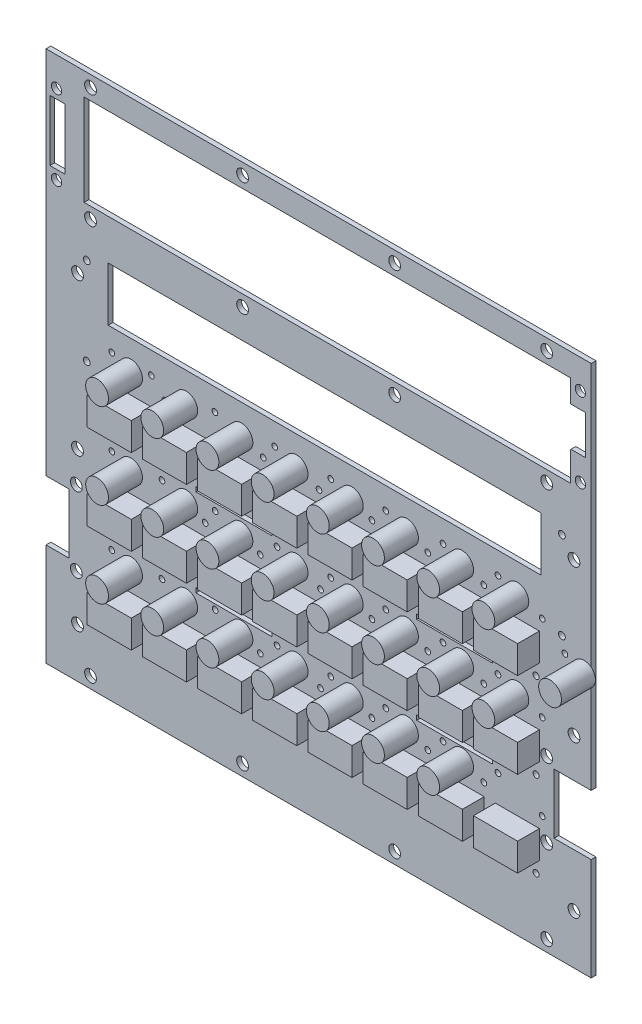
SolidWorks part; units mm, degrees
ref_plane "Front Plane" through (0, 0, 0) normal (0, 0, 1) x (1, 0, 0)
ref_plane "Top Plane" through (0, 0, 0) normal (0, 1, 0) x (1, 0, 0)
ref_plane "Right Plane" through (0, 0, 0) normal (1, 0, 0) x (0, 0, -1)
sketch "Sketch1" plane through (0, 0, 0) normal (0, 0, 1) x (1, 0, 0)
  line L0 (0, 0) -> (182.118, 0)
  line L1 (182.118, 0) -> (182.118, 34.2468)
  line L2 (182.118, 34.2468) -> (169.7355, 34.2468)
  line L3 (169.7355, 34.2468) -> (169.7355, 54.2468)
  line L4 (169.7355, 54.2468) -> (182.118, 54.2468)
  line L5 (182.118, 54.2468) -> (182.118, 177.8)
  line L6 (182.118, 177.8) -> (0, 177.8)
  line L7 (0, 177.8) -> (0, 54.2468)
  line L8 (0, 54.2468) -> (7.62, 54.2468)
  line L9 (7.62, 54.2468) -> (7.62, 34.2468)
  line L10 (7.62, 34.2468) -> (0, 34.2468)
  line L11 (0, 34.2468) -> (0, 0)
  line L12 (20.7391, 108.1786) -> (20.7391, 126.1796)
  line L13 (20.7391, 126.1796) -> (165.3007, 126.1796)
  line L14 (165.3007, 126.1796) -> (165.3007, 108.1786)
  line L15 (165.3007, 108.1786) -> (20.7391, 108.1786)
  line L16 (1.27, 144.653) -> (1.27, 164.973)
  line L17 (1.27, 164.973) -> (6.35, 164.973)
  line L18 (6.35, 164.973) -> (6.35, 144.653)
  line L19 (6.35, 144.653) -> (1.27, 144.653)
  line L20 (12.7, 139.7) -> (12.7, 170.18)
  line L21 (12.7, 170.18) -> (175.26, 170.18)
  line L22 (175.26, 170.18) -> (175.26, 162.6616)
  line L23 (175.26, 162.6616) -> (180.086, 162.6616)
  line L24 (180.086, 162.6616) -> (180.2892, 162.4584)
  line L25 (180.2892, 162.4584) -> (180.2892, 149.606)
  line L26 (180.2892, 149.606) -> (175.3616, 149.606)
  line L27 (175.3616, 149.606) -> (175.26, 149.5044)
  line L28 (175.26, 149.5044) -> (175.26, 139.7)
  line L29 (175.26, 139.7) -> (12.7, 139.7)
  line L30 (50.0634, 45.4152) -> (50.0634, 47.0027)
  line L31 (50.0634, 47.0027) -> (75.4634, 47.0027)
  line L32 (75.4634, 47.0027) -> (75.4634, 45.4152)
  line L33 (75.4634, 45.4152) -> (50.0634, 45.4152)
  line L34 (123.8134, 45.4152) -> (123.8134, 47.0027)
  line L35 (123.8134, 47.0027) -> (149.2134, 47.0027)
  line L36 (149.2134, 47.0027) -> (149.2134, 45.4152)
  line L37 (149.2134, 45.4152) -> (123.8134, 45.4152)
  line L38 (123.8134, 74.6252) -> (123.8134, 76.2127)
  line L39 (123.8134, 76.2127) -> (149.2134, 76.2127)
  line L40 (149.2134, 76.2127) -> (149.2134, 74.6252)
  line L41 (149.2134, 74.6252) -> (123.8134, 74.6252)
  line L42 (50.0634, 74.6252) -> (50.0634, 76.2127)
  line L43 (50.0634, 76.2127) -> (75.4634, 76.2127)
  line L44 (75.4634, 76.2127) -> (75.4634, 74.6252)
  line L45 (75.4634, 74.6252) -> (50.0634, 74.6252)
extrude "BOARD" add sketch "Sketch1" along normal blind 1.5921 separate body
ref_plane "Plane1" through (0, 0, 1.5921) normal (0, 0, 1) x (1, 0, 0)
sketch "Sketch2" plane through (0, 0, 1.5921) normal (0, 0, 1) x (1, 0, 0)
  circle A0 centre (179.7355, 86.9188) radius 3.81
extrude "LED-KINGBRIGHT_3P_2P54-1" add sketch "Sketch2" along normal blind 11.3538 separate body
sketch "Sketch4" plane through (0, 0, 1.5921) normal (0, 0, 1) x (1, 0, 0)
  circle A0 centre (139.0222, 41.1988) radius 3.81
extrude "LED-KINGBRIGHT_3P_2P54-3" add sketch "Sketch4" along normal blind 11.3538 separate body
sketch "Sketch5" plane through (0, 0, 1.5921) normal (0, 0, 1) x (1, 0, 0)
  circle A0 centre (120.5847, 41.1988) radius 3.81
extrude "LED-KINGBRIGHT_3P_2P54-4" add sketch "Sketch5" along normal blind 11.3538 separate body
sketch "Sketch6" plane through (0, 0, 1.5921) normal (0, 0, 1) x (1, 0, 0)
  circle A0 centre (102.1472, 41.1988) radius 3.81
extrude "LED-KINGBRIGHT_3P_2P54-5" add sketch "Sketch6" along normal blind 11.3538 separate body
sketch "Sketch7" plane through (0, 0, 1.5921) normal (0, 0, 1) x (1, 0, 0)
  circle A0 centre (157.4597, 69.7738) radius 3.81
extrude "LED-KINGBRIGHT_3P_2P54-6" add sketch "Sketch7" along normal blind 11.3538 separate body
sketch "Sketch8" plane through (0, 0, 1.5921) normal (0, 0, 1) x (1, 0, 0)
  circle A0 centre (139.0222, 69.7738) radius 3.81
extrude "LED-KINGBRIGHT_3P_2P54-7" add sketch "Sketch8" along normal blind 11.3538 separate body
sketch "Sketch9" plane through (0, 0, 1.5921) normal (0, 0, 1) x (1, 0, 0)
  circle A0 centre (120.5847, 69.7738) radius 3.81
extrude "LED-KINGBRIGHT_3P_2P54-8" add sketch "Sketch9" along normal blind 11.3538 separate body
sketch "Sketch10" plane through (0, 0, 1.5921) normal (0, 0, 1) x (1, 0, 0)
  circle A0 centre (102.1472, 69.7738) radius 3.81
extrude "LED-KINGBRIGHT_3P_2P54-9" add sketch "Sketch10" along normal blind 11.3538 separate body
sketch "Sketch11" plane through (0, 0, 1.5921) normal (0, 0, 1) x (1, 0, 0)
  circle A0 centre (83.7097, 41.1988) radius 3.81
extrude "LED-KINGBRIGHT_3P_2P54-10" add sketch "Sketch11" along normal blind 11.3538 separate body
sketch "Sketch12" plane through (0, 0, 1.5921) normal (0, 0, 1) x (1, 0, 0)
  circle A0 centre (65.2722, 41.1988) radius 3.81
extrude "LED-KINGBRIGHT_3P_2P54-11" add sketch "Sketch12" along normal blind 11.3538 separate body
sketch "Sketch13" plane through (0, 0, 1.5921) normal (0, 0, 1) x (1, 0, 0)
  circle A0 centre (46.8347, 41.1988) radius 3.81
extrude "LED-KINGBRIGHT_3P_2P54-12" add sketch "Sketch13" along normal blind 11.3538 separate body
sketch "Sketch14" plane through (0, 0, 1.5921) normal (0, 0, 1) x (1, 0, 0)
  circle A0 centre (28.3972, 41.1988) radius 3.81
extrude "LED-KINGBRIGHT_3P_2P54-13" add sketch "Sketch14" along normal blind 11.3538 separate body
sketch "Sketch15" plane through (0, 0, 1.5921) normal (0, 0, 1) x (1, 0, 0)
  circle A0 centre (83.7097, 69.7738) radius 3.81
extrude "LED-KINGBRIGHT_3P_2P54-14" add sketch "Sketch15" along normal blind 11.3538 separate body
sketch "Sketch16" plane through (0, 0, 1.5921) normal (0, 0, 1) x (1, 0, 0)
  circle A0 centre (65.2722, 69.7738) radius 3.81
extrude "LED-KINGBRIGHT_3P_2P54-15" add sketch "Sketch16" along normal blind 11.3538 separate body
sketch "Sketch17" plane through (0, 0, 1.5921) normal (0, 0, 1) x (1, 0, 0)
  circle A0 centre (46.8347, 69.7738) radius 3.81
extrude "LED-KINGBRIGHT_3P_2P54-16" add sketch "Sketch17" along normal blind 11.3538 separate body
sketch "Sketch18" plane through (0, 0, 1.5921) normal (0, 0, 1) x (1, 0, 0)
  circle A0 centre (28.3972, 69.7738) radius 3.81
extrude "LED-KINGBRIGHT_3P_2P54-17" add sketch "Sketch18" along normal blind 11.3538 separate body
sketch "Sketch19" plane through (0, 0, 1.5921) normal (0, 0, 1) x (1, 0, 0)
  circle A0 centre (157.4597, 98.3488) radius 3.81
extrude "LED-KINGBRIGHT_3P_2P54-18" add sketch "Sketch19" along normal blind 11.3538 separate body
sketch "Sketch20" plane through (0, 0, 1.5921) normal (0, 0, 1) x (1, 0, 0)
  circle A0 centre (139.0222, 98.3488) radius 3.81
extrude "LED-KINGBRIGHT_3P_2P54-19" add sketch "Sketch20" along normal blind 11.3538 separate body
sketch "Sketch21" plane through (0, 0, 1.5921) normal (0, 0, 1) x (1, 0, 0)
  circle A0 centre (120.5847, 98.3488) radius 3.81
extrude "LED-KINGBRIGHT_3P_2P54-20" add sketch "Sketch21" along normal blind 11.3538 separate body
sketch "Sketch22" plane through (0, 0, 1.5921) normal (0, 0, 1) x (1, 0, 0)
  circle A0 centre (102.1472, 98.3488) radius 3.81
extrude "LED-KINGBRIGHT_3P_2P54-21" add sketch "Sketch22" along normal blind 11.3538 separate body
sketch "Sketch23" plane through (0, 0, 1.5921) normal (0, 0, 1) x (1, 0, 0)
  circle A0 centre (83.7097, 98.3488) radius 3.81
extrude "LED-KINGBRIGHT_3P_2P54-22" add sketch "Sketch23" along normal blind 11.3538 separate body
sketch "Sketch24" plane through (0, 0, 1.5921) normal (0, 0, 1) x (1, 0, 0)
  circle A0 centre (65.2722, 98.3488) radius 3.81
extrude "LED-KINGBRIGHT_3P_2P54-23" add sketch "Sketch24" along normal blind 11.3538 separate body
sketch "Sketch25" plane through (0, 0, 1.5921) normal (0, 0, 1) x (1, 0, 0)
  circle A0 centre (46.8347, 98.3488) radius 3.81
extrude "LED-KINGBRIGHT_3P_2P54-24" add sketch "Sketch25" along normal blind 11.3538 separate body
sketch "Sketch26" plane through (0, 0, 1.5921) normal (0, 0, 1) x (1, 0, 0)
  circle A0 centre (28.3972, 98.3488) radius 3.81
extrude "LED-KINGBRIGHT_3P_2P54-25" add sketch "Sketch26" along normal blind 11.3538 separate body
sketch "Sketch27" plane through (0, 0, 1.5921) normal (0, 0, 1) x (1, 0, 0)
  line L0 (150.0937, 25.3238) -> (150.0937, 34.5948)
  line L1 (150.0937, 34.5948) -> (164.8257, 34.5948)
  line L2 (164.8257, 34.5948) -> (164.8257, 25.3238)
  line L3 (164.8257, 25.3238) -> (150.0937, 25.3238)
extrude "SWITCH-MCDTS2-1" add sketch "Sketch27" along normal blind 7.3 separate body
sketch "Sketch28" plane through (0, 0, 1.5921) normal (0, 0, 1) x (1, 0, 0)
  line L0 (150.0937, 53.8988) -> (150.0937, 63.1698)
  line L1 (150.0937, 63.1698) -> (164.8257, 63.1698)
  line L2 (164.8257, 63.1698) -> (164.8257, 53.8988)
  line L3 (164.8257, 53.8988) -> (150.0937, 53.8988)
extrude "SWITCH-MCDTS2-2" add sketch "Sketch28" along normal blind 7.3 separate body
sketch "Sketch29" plane through (0, 0, 1.5921) normal (0, 0, 1) x (1, 0, 0)
  line L0 (131.6562, 25.3238) -> (131.6562, 34.5948)
  line L1 (131.6562, 34.5948) -> (146.3882, 34.5948)
  line L2 (146.3882, 34.5948) -> (146.3882, 25.3238)
  line L3 (146.3882, 25.3238) -> (131.6562, 25.3238)
extrude "SWITCH-MCDTS2-3" add sketch "Sketch29" along normal blind 7.3 separate body
sketch "Sketch30" plane through (0, 0, 1.5921) normal (0, 0, 1) x (1, 0, 0)
  line L0 (113.2187, 25.3238) -> (113.2187, 34.5948)
  line L1 (113.2187, 34.5948) -> (127.9507, 34.5948)
  line L2 (127.9507, 34.5948) -> (127.9507, 25.3238)
  line L3 (127.9507, 25.3238) -> (113.2187, 25.3238)
extrude "SWITCH-MCDTS2-4" add sketch "Sketch30" along normal blind 7.3 separate body
sketch "Sketch31" plane through (0, 0, 1.5921) normal (0, 0, 1) x (1, 0, 0)
  line L0 (94.7812, 25.3238) -> (94.7812, 34.5948)
  line L1 (94.7812, 34.5948) -> (109.5132, 34.5948)
  line L2 (109.5132, 34.5948) -> (109.5132, 25.3238)
  line L3 (109.5132, 25.3238) -> (94.7812, 25.3238)
extrude "SWITCH-MCDTS2-5" add sketch "Sketch31" along normal blind 7.3 separate body
sketch "Sketch32" plane through (0, 0, 1.5921) normal (0, 0, 1) x (1, 0, 0)
  line L0 (76.3437, 25.3238) -> (76.3437, 34.5948)
  line L1 (76.3437, 34.5948) -> (91.0757, 34.5948)
  line L2 (91.0757, 34.5948) -> (91.0757, 25.3238)
  line L3 (91.0757, 25.3238) -> (76.3437, 25.3238)
extrude "SWITCH-MCDTS2-6" add sketch "Sketch32" along normal blind 7.3 separate body
sketch "Sketch33" plane through (0, 0, 1.5921) normal (0, 0, 1) x (1, 0, 0)
  line L0 (57.9062, 25.3238) -> (57.9062, 34.5948)
  line L1 (57.9062, 34.5948) -> (72.6382, 34.5948)
  line L2 (72.6382, 34.5948) -> (72.6382, 25.3238)
  line L3 (72.6382, 25.3238) -> (57.9062, 25.3238)
extrude "SWITCH-MCDTS2-7" add sketch "Sketch33" along normal blind 7.3 separate body
sketch "Sketch34" plane through (0, 0, 1.5921) normal (0, 0, 1) x (1, 0, 0)
  line L0 (39.4687, 25.3238) -> (39.4687, 34.5948)
  line L1 (39.4687, 34.5948) -> (54.2007, 34.5948)
  line L2 (54.2007, 34.5948) -> (54.2007, 25.3238)
  line L3 (54.2007, 25.3238) -> (39.4687, 25.3238)
extrude "SWITCH-MCDTS2-8" add sketch "Sketch34" along normal blind 7.3 separate body
sketch "Sketch35" plane through (0, 0, 1.5921) normal (0, 0, 1) x (1, 0, 0)
  line L0 (21.0312, 25.3238) -> (21.0312, 34.5948)
  line L1 (21.0312, 34.5948) -> (35.7632, 34.5948)
  line L2 (35.7632, 34.5948) -> (35.7632, 25.3238)
  line L3 (35.7632, 25.3238) -> (21.0312, 25.3238)
extrude "SWITCH-MCDTS2-9" add sketch "Sketch35" along normal blind 7.3 separate body
sketch "Sketch36" plane through (0, 0, 1.5921) normal (0, 0, 1) x (1, 0, 0)
  line L0 (131.6562, 53.8988) -> (131.6562, 63.1698)
  line L1 (131.6562, 63.1698) -> (146.3882, 63.1698)
  line L2 (146.3882, 63.1698) -> (146.3882, 53.8988)
  line L3 (146.3882, 53.8988) -> (131.6562, 53.8988)
extrude "SWITCH-MCDTS2-10" add sketch "Sketch36" along normal blind 7.3 separate body
sketch "Sketch37" plane through (0, 0, 1.5921) normal (0, 0, 1) x (1, 0, 0)
  line L0 (113.2187, 53.8988) -> (113.2187, 63.1698)
  line L1 (113.2187, 63.1698) -> (127.9507, 63.1698)
  line L2 (127.9507, 63.1698) -> (127.9507, 53.8988)
  line L3 (127.9507, 53.8988) -> (113.2187, 53.8988)
extrude "SWITCH-MCDTS2-11" add sketch "Sketch37" along normal blind 7.3 separate body
sketch "Sketch38" plane through (0, 0, 1.5921) normal (0, 0, 1) x (1, 0, 0)
  line L0 (94.7812, 53.8988) -> (94.7812, 63.1698)
  line L1 (94.7812, 63.1698) -> (109.5132, 63.1698)
  line L2 (109.5132, 63.1698) -> (109.5132, 53.8988)
  line L3 (109.5132, 53.8988) -> (94.7812, 53.8988)
extrude "SWITCH-MCDTS2-12" add sketch "Sketch38" along normal blind 7.3 separate body
sketch "Sketch39" plane through (0, 0, 1.5921) normal (0, 0, 1) x (1, 0, 0)
  line L0 (76.3437, 53.8988) -> (76.3437, 63.1698)
  line L1 (76.3437, 63.1698) -> (91.0757, 63.1698)
  line L2 (91.0757, 63.1698) -> (91.0757, 53.8988)
  line L3 (91.0757, 53.8988) -> (76.3437, 53.8988)
extrude "SWITCH-MCDTS2-13" add sketch "Sketch39" along normal blind 7.3 separate body
sketch "Sketch40" plane through (0, 0, 1.5921) normal (0, 0, 1) x (1, 0, 0)
  line L0 (57.9062, 53.8988) -> (57.9062, 63.1698)
  line L1 (57.9062, 63.1698) -> (72.6382, 63.1698)
  line L2 (72.6382, 63.1698) -> (72.6382, 53.8988)
  line L3 (72.6382, 53.8988) -> (57.9062, 53.8988)
extrude "SWITCH-MCDTS2-14" add sketch "Sketch40" along normal blind 7.3 separate body
sketch "Sketch41" plane through (0, 0, 1.5921) normal (0, 0, 1) x (1, 0, 0)
  line L0 (39.4687, 53.8988) -> (39.4687, 63.1698)
  line L1 (39.4687, 63.1698) -> (54.2007, 63.1698)
  line L2 (54.2007, 63.1698) -> (54.2007, 53.8988)
  line L3 (54.2007, 53.8988) -> (39.4687, 53.8988)
extrude "SWITCH-MCDTS2-15" add sketch "Sketch41" along normal blind 7.3 separate body
sketch "Sketch42" plane through (0, 0, 1.5921) normal (0, 0, 1) x (1, 0, 0)
  line L0 (21.0312, 53.8988) -> (21.0312, 63.1698)
  line L1 (21.0312, 63.1698) -> (35.7632, 63.1698)
  line L2 (35.7632, 63.1698) -> (35.7632, 53.8988)
  line L3 (35.7632, 53.8988) -> (21.0312, 53.8988)
extrude "SWITCH-MCDTS2-16" add sketch "Sketch42" along normal blind 7.3 separate body
sketch "Sketch43" plane through (0, 0, 1.5921) normal (0, 0, 1) x (1, 0, 0)
  line L0 (150.0937, 82.4738) -> (150.0937, 91.7448)
  line L1 (150.0937, 91.7448) -> (164.8257, 91.7448)
  line L2 (164.8257, 91.7448) -> (164.8257, 82.4738)
  line L3 (164.8257, 82.4738) -> (150.0937, 82.4738)
extrude "SWITCH-MCDTS2-17" add sketch "Sketch43" along normal blind 7.3 separate body
sketch "Sketch44" plane through (0, 0, 1.5921) normal (0, 0, 1) x (1, 0, 0)
  line L0 (131.6562, 82.4738) -> (131.6562, 91.7448)
  line L1 (131.6562, 91.7448) -> (146.3882, 91.7448)
  line L2 (146.3882, 91.7448) -> (146.3882, 82.4738)
  line L3 (146.3882, 82.4738) -> (131.6562, 82.4738)
extrude "SWITCH-MCDTS2-18" add sketch "Sketch44" along normal blind 7.3 separate body
sketch "Sketch45" plane through (0, 0, 1.5921) normal (0, 0, 1) x (1, 0, 0)
  line L0 (113.2187, 82.4738) -> (113.2187, 91.7448)
  line L1 (113.2187, 91.7448) -> (127.9507, 91.7448)
  line L2 (127.9507, 91.7448) -> (127.9507, 82.4738)
  line L3 (127.9507, 82.4738) -> (113.2187, 82.4738)
extrude "SWITCH-MCDTS2-19" add sketch "Sketch45" along normal blind 7.3 separate body
sketch "Sketch46" plane through (0, 0, 1.5921) normal (0, 0, 1) x (1, 0, 0)
  line L0 (94.7812, 82.4738) -> (94.7812, 91.7448)
  line L1 (94.7812, 91.7448) -> (109.5132, 91.7448)
  line L2 (109.5132, 91.7448) -> (109.5132, 82.4738)
  line L3 (109.5132, 82.4738) -> (94.7812, 82.4738)
extrude "SWITCH-MCDTS2-20" add sketch "Sketch46" along normal blind 7.3 separate body
sketch "Sketch47" plane through (0, 0, 1.5921) normal (0, 0, 1) x (1, 0, 0)
  line L0 (76.3437, 82.4738) -> (76.3437, 91.7448)
  line L1 (76.3437, 91.7448) -> (91.0757, 91.7448)
  line L2 (91.0757, 91.7448) -> (91.0757, 82.4738)
  line L3 (91.0757, 82.4738) -> (76.3437, 82.4738)
extrude "SWITCH-MCDTS2-21" add sketch "Sketch47" along normal blind 7.3 separate body
sketch "Sketch48" plane through (0, 0, 1.5921) normal (0, 0, 1) x (1, 0, 0)
  line L0 (57.9062, 82.4738) -> (57.9062, 91.7448)
  line L1 (57.9062, 91.7448) -> (72.6382, 91.7448)
  line L2 (72.6382, 91.7448) -> (72.6382, 82.4738)
  line L3 (72.6382, 82.4738) -> (57.9062, 82.4738)
extrude "SWITCH-MCDTS2-22" add sketch "Sketch48" along normal blind 7.3 separate body
sketch "Sketch49" plane through (0, 0, 1.5921) normal (0, 0, 1) x (1, 0, 0)
  line L0 (39.4687, 82.4738) -> (39.4687, 91.7448)
  line L1 (39.4687, 91.7448) -> (54.2007, 91.7448)
  line L2 (54.2007, 91.7448) -> (54.2007, 82.4738)
  line L3 (54.2007, 82.4738) -> (39.4687, 82.4738)
extrude "SWITCH-MCDTS2-23" add sketch "Sketch49" along normal blind 7.3 separate body
sketch "Sketch50" plane through (0, 0, 1.5921) normal (0, 0, 1) x (1, 0, 0)
  line L0 (21.0312, 82.4738) -> (21.0312, 91.7448)
  line L1 (21.0312, 91.7448) -> (35.7632, 91.7448)
  line L2 (35.7632, 91.7448) -> (35.7632, 82.4738)
  line L3 (35.7632, 82.4738) -> (21.0312, 82.4738)
extrude "SWITCH-MCDTS2-24" add sketch "Sketch50" along normal blind 7.3 separate body
sketch "Sketch59" plane through (0, 0, 1.5921) normal (0, 0, 1) x (1, 0, 0)
  circle B0 centre (163.703, 21.1074) radius 1.016
  circle B1 centre (163.703, 49.6824) radius 1.016
  circle B2 centre (145.2626, 21.8186) radius 0.9652
  circle B3 centre (126.8476, 21.6154) radius 0.9652
  circle B4 centre (108.4072, 21.7424) radius 0.9652
  circle B5 centre (89.9668, 21.844) radius 0.9652
  circle B6 centre (71.5264, 20.7772) radius 0.9652
  circle B7 centre (53.086, 21.1582) radius 0.9652
  circle B8 centre (34.6472, 21.1328) radius 1.016
  circle B9 centre (145.2626, 49.5554) radius 1.016
  circle B10 centre (126.8222, 49.3522) radius 1.016
  circle B11 centre (108.3818, 49.1236) radius 1.016
  circle B12 centre (89.9414, 49.6824) radius 1.016
  circle B13 centre (71.501, 49.1998) radius 1.016
  circle B14 centre (53.0606, 49.1998) radius 1.016
  circle B15 centre (34.6202, 49.276) radius 1.016
  circle B16 centre (163.703, 78.2574) radius 1.016
  circle B17 centre (145.2626, 77.7748) radius 1.016
  circle B18 centre (126.746, 78.3336) radius 1.016
  circle B19 centre (108.3818, 78.74) radius 1.016
  circle B20 centre (89.9414, 78.3336) radius 1.016
  circle B21 centre (71.501, 78.2574) radius 1.016
  circle B22 centre (53.0606, 78.4098) radius 1.016
  circle B23 centre (34.6202, 78.0542) radius 1.016
  circle B24 centre (91.694, 38.6588) radius 0.9525
  circle B25 centre (77.1652, 43.7388) radius 0.9525
  circle B26 centre (71.5772, 38.6588) radius 0.9525
  circle B27 centre (56.4896, 43.7388) radius 0.9525
  circle B28 centre (38.735, 43.7388) radius 0.9525
  circle B29 centre (21.8948, 38.6588) radius 0.9525
  circle B30 centre (21.971, 43.7388) radius 0.9525
  circle B31 centre (77.1652, 72.3138) radius 0.9525
  circle B32 centre (91.694, 67.2338) radius 0.9525
  circle B33 centre (71.5772, 67.2338) radius 0.9525
  circle B34 centre (56.4896, 72.3138) radius 0.9525
  circle B35 centre (53.1368, 67.2338) radius 0.9525
  circle B36 centre (38.735, 72.3138) radius 0.9525
  circle B37 centre (21.8948, 67.2338) radius 0.9525
  circle B38 centre (21.971, 72.3138) radius 0.9525
  circle B39 centre (165.735, 95.8088) radius 0.9525
  circle B40 centre (150.9776, 100.8888) radius 0.9525
  circle B41 centre (146.2278, 95.8088) radius 0.9525
  circle B42 centre (132.6134, 100.8888) radius 0.9525
  circle B43 centre (113.4872, 100.8888) radius 0.9525
  circle B44 centre (127.508, 95.8088) radius 0.9525
  circle B45 centre (108.8644, 95.8088) radius 0.9525
  circle B46 centre (95.0976, 100.8888) radius 0.9525
  circle B47 centre (91.186, 95.8088) radius 0.9525
  circle B48 centre (76.3778, 100.8888) radius 0.9525
  circle B49 centre (72.5424, 95.8088) radius 0.9525
  circle B50 centre (56.4134, 100.8888) radius 0.9525
  circle B51 centre (39.7256, 95.8088) radius 0.9525
  circle B52 centre (35.179, 100.8888) radius 0.9525
  circle B53 centre (24.2062, 95.8088) radius 0.9525
  circle B54 centre (21.971, 100.8888) radius 0.9525
  circle B55 centre (132.6134, 72.3138) radius 0.9525
  circle B56 centre (146.2278, 67.2338) radius 0.9525
  circle B57 centre (113.4872, 72.3138) radius 0.9525
  circle B58 centre (127.508, 67.2338) radius 0.9525
  circle B59 centre (95.0976, 72.3138) radius 0.9525
  circle B60 centre (108.8644, 67.2338) radius 0.9525
  circle B61 centre (173.3296, 89.4588) radius 0.9525
  circle B62 centre (150.9776, 43.7388) radius 0.9525
  circle B63 centre (132.6134, 43.7388) radius 0.9525
  circle B64 centre (113.4872, 43.7388) radius 0.9525
  circle B65 centre (95.0976, 43.7388) radius 0.9525
  circle B66 centre (108.8644, 38.6588) radius 0.9525
  circle B67 centre (150.9776, 72.3138) radius 0.9525
  circle B68 centre (165.735, 67.2338) radius 0.9525
  circle B69 centre (173.355, 84.3534) radius 0.9525
  circle B70 centre (176.3725, 118.11) radius 1.9685
  circle B71 centre (176.3725, 67.31) radius 1.9685
  circle B72 centre (176.3725, 16.51) radius 1.9685
  circle B73 centre (167.259, 135.89) radius 1.9685
  circle B74 centre (116.459, 135.89) radius 1.9685
  circle B75 centre (65.659, 135.89) radius 1.9685
  circle B76 centre (14.859, 135.89) radius 1.9685
  circle B77 centre (10.5105, 118.11) radius 1.9685
  circle B78 centre (10.5105, 67.31) radius 1.9685
  circle B79 centre (10.5105, 16.51) radius 1.9685
  circle B80 centre (165.735, 38.6588) radius 0.9525
  circle B81 centre (146.2278, 38.6588) radius 0.9525
  circle B82 centre (127.508, 38.6588) radius 0.9525
  circle B83 centre (14.859, 173.99) radius 1.9685
  circle B84 centre (65.659, 173.99) radius 1.9685
  circle B85 centre (116.459, 173.99) radius 1.9685
  circle B86 centre (167.259, 173.99) radius 1.9685
  circle B87 centre (167.259, 3.81) radius 1.9685
  circle B88 centre (116.459, 3.81) radius 1.9685
  circle B89 centre (65.659, 3.81) radius 1.9685
  circle B90 centre (14.859, 3.81) radius 1.9685
  circle B91 centre (167.2336, 56.7436) radius 1.9685
  circle B92 centre (167.2336, 31.75) radius 1.9685
  circle B93 centre (10.1168, 56.7436) radius 1.9685
  circle B94 centre (10.1168, 31.75) radius 1.9685
  circle B95 centre (172.3415, 123.3754) radius 1.1303
  circle B96 centre (172.3415, 94.1654) radius 1.1303
  circle B97 centre (13.5915, 94.1654) radius 1.1303
  circle B98 centre (13.5915, 123.3754) radius 1.1303
  circle B99 centre (178.5137, 141.5618) radius 1.7145
  circle B100 centre (178.5137, 168.0616) radius 1.7145
  circle B101 centre (3.5001, 168.0616) radius 1.7145
  circle B102 centre (3.5001, 141.5618) radius 1.7145
sketch_block_instance "Block-Block4-1"
sketch_block "Block-Block4"
extrude "Cut-Extrude1" cut sketch "Sketch59" against normal blind 10
